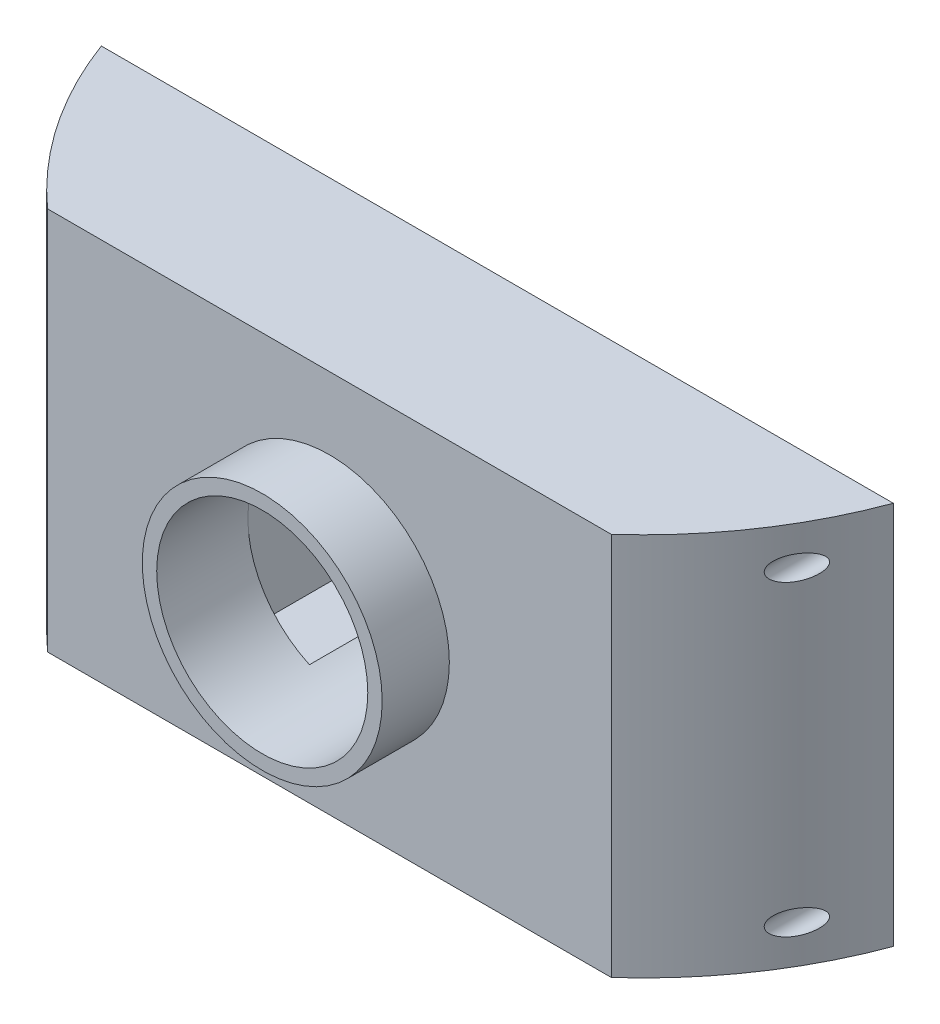
SolidWorks part; units mm, degrees
ref_plane "Спереди" through (0, 0, 0) normal (0, 0, 1) x (1, 0, 0)
ref_plane "Сверху" through (0, 0, 0) normal (0, 1, 0) x (1, 0, 0)
ref_plane "Справа" through (0, 0, 0) normal (1, 0, 0) x (0, 0, -1)
sketch "Эскиз1" plane through (0, 0, 0) normal (0, 0, 1) x (1, 0, 0)
  line L1 (0, 0) -> (85, 0)
  line L2 (0, 0) -> (0, -40)
  line L3 (0, -40) -> (85, -40)
  line L4 (85, 0) -> (85, -40)
  dimension "D1" = 40
  dimension "D2" = 85
extrude "Бобышка-Вытянуть1" add sketch "Эскиз1" along normal blind 17.5
sketch "Эскиз2" plane through (0, 0, 0) normal (0, 0, 1) x (1, 0, 0)
  line L0 (0, 0) -> (0, -40) construction
  line L1 (25.5, -10) -> (79.5, -10)
  line L2 (25.5, -10) -> (25.5, -30)
  line L3 (25.5, -30) -> (79.5, -30)
  line L4 (79.5, -10) -> (79.5, -30)
  line L5 (0, -40) -> (85, -40) construction
  point P6 (0, -20)
  dimension "D1" = 20
  dimension "D2" = 54
  dimension "D3" = 25.5
  dimension "D4" = 10
extrude "Вырез-Вытянуть1" cut sketch "Эскиз2" along normal blind 4
sketch "Эскиз3" plane through (0, 0, 0) normal (0, 0, 1) x (1, 0, 0)
  line L0 (0, 0) -> (0, -40) construction
  line L1 (85, 0) -> (0, 0) construction
  circle A0 centre (42.5, -20) radius 11
  dimension "D1" = 22
  dimension "D2" = 42.5
  dimension "D3" = 20
extrude "Вырез-Вытянуть2" cut sketch "Эскиз3" along normal through all
sketch "Эскиз4" plane through (0, 0, 0) normal (0, 0, 1) x (1, 0, 0)
  line L0 (85, 0) -> (0, 0) construction
  line L1 (31.5, -10) -> (72.5, -10)
  line L2 (31.5, -10) -> (31.5, -30)
  line L3 (31.5, -30) -> (72.5, -30)
  line L4 (72.5, -10) -> (72.5, -30)
  line L6 (0, 0) -> (0, -40) construction
  dimension "D1" = 20
  dimension "D2" = 41
  dimension "D3" = 10
  dimension "D4" = 31.5
extrude "Вырез-Вытянуть3" cut sketch "Эскиз4" along normal blind 15
sketch "Эскиз6" plane through (0, -40, 0) normal (0, -1, 0) x (1, 0, 0)
  line L2 (0, 17.5) -> (13.1263, 17.5)
  line L4 (71.8737, 17.5) -> (85, 17.5)
  line L6 (85, 0) -> (85, 17.5)
  line L7 (83.7692, 0) -> (85, 0)
  line L8 (0, 17.5) -> (0, 0)
  line L9 (0, 0) -> (1.2308, 0)
  line L10 (0, 0) -> (85, 0) construction
  arc A0 (1.2308, 0) -> (13.1263, 17.5) centre (42.5, -15.2595) cw
  arc A1 (83.7692, 0) -> (71.8737, 17.5) centre (42.5, -15.2595) ccw
  dimension "D1" = 44
  dimension "D2" = 44
extrude "Вырез-Вытянуть4" cut sketch "Эскиз6" against normal up to surface (40 mm away) up to face at (42.5, 0, 8.75)
sketch "Эскиз8" plane through (0, 0, 17.5) normal (0, 0, 1) x (1, 0, 0)
  circle A1 centre (42.5, -20) radius 12.5
  circle A2 centre (42.5, -20) radius 11 construction
  circle A3 centre (42.5, -20) radius 11
  dimension "D1" = 22
  dimension "D3" = 25
sketch "Эскиз10" plane through (0, 0, 4) normal (0, 0, -1) x (-1, 0, 0)
  line L0 (-37.9174, -10) -> (-25.5, -10) construction
  line L1 (-25.5, -10) -> (-25.5, -30) construction
  line L2 (-25.5, -30) -> (-31.5, -30) construction
  line L3 (-25.5, -10) -> (-25.5, -30) construction
  line L4 (-79.5, -30) -> (-79.5, -10) construction
  line L5 (-79.5, -30) -> (-79.5, -10) construction
  line L6 (-79.5, -10) -> (-72.5, -10) construction
  line L7 (-72.5, -30) -> (-79.5, -30) construction
  circle A0 centre (-28.5, -15) radius 2
  circle A1 centre (-28.5, -25) radius 2
  circle A2 centre (-76.5, -15) radius 2
  circle A3 centre (-76.5, -25) radius 2
  dimension "D1" = 4
  dimension "D2" = 4
  dimension "D7" = 4
  dimension "D8" = 4
  dimension "D3" = 5
  dimension "D4" = 3
  dimension "D5" = 5
  dimension "D6" = 3
  dimension "D9" = 3
  dimension "D10" = 3
  dimension "D11" = 5
  dimension "D12" = 5
extrude "Вырез-Вытянуть7" cut sketch "Эскиз10" against normal blind 3
extrude "Бобышка-Вытянуть2" add sketch "Эскиз8" along normal blind 7
sketch "Эскиз12" plane through (0, 0, 0) normal (0, 0, 1) x (1, 0, 0)
  line L1 (4.5, -4) -> (80.5, -4) construction
  line L2 (4.5, -4) -> (4.5, -36) construction
  line L3 (4.5, -36) -> (80.5, -36) construction
  line L4 (80.5, -4) -> (80.5, -36) construction
  circle A0 centre (42.5, -20) radius 11 construction
  arc A1 (31.5, -20) -> (37.9174, -30) centre (42.5, -20) ccw construction
  circle A2 centre (80.5, -4) radius 1.25
  circle A3 centre (80.5, -36) radius 1.25
  circle A4 centre (4.5, -36) radius 1.25
  circle A5 centre (4.5, -4) radius 1.25
  dimension "D5" = 2.5
  dimension "D6" = 2.5
  dimension "D7" = 2.5
  dimension "D8" = 2.5
  dimension "D1" = 76
  dimension "D2" = 38
  dimension "D3" = 32
  dimension "D4" = 16
extrude "Вырез-Вытянуть10" cut sketch "Эскиз12" along normal through all
